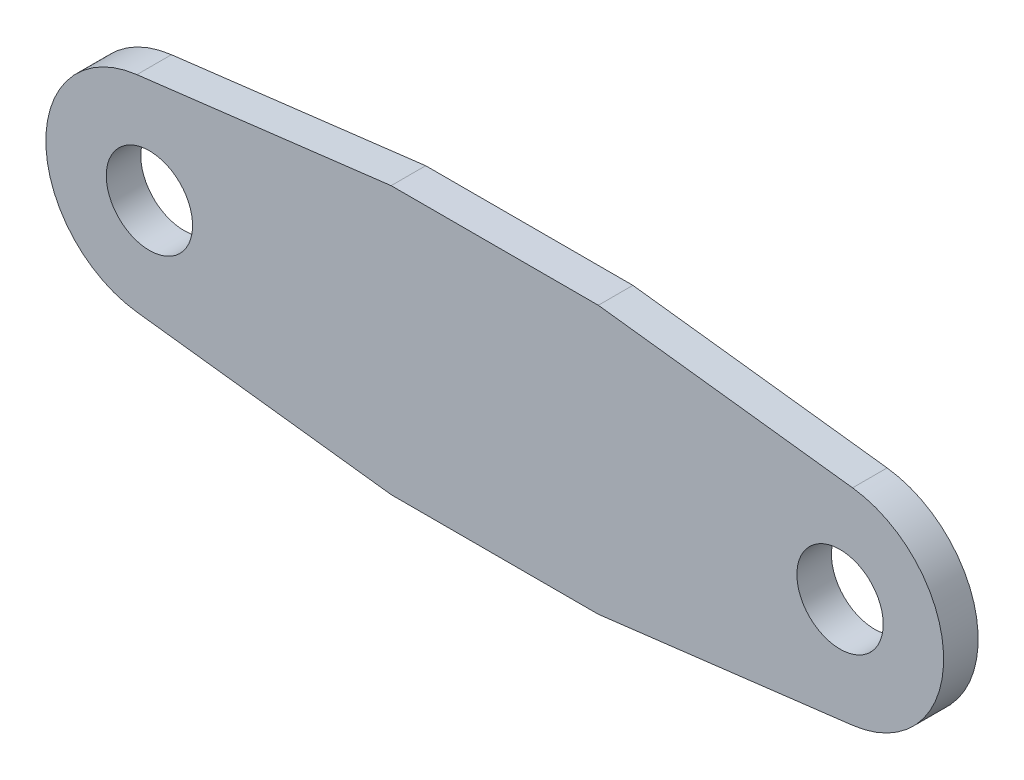
SolidWorks part; units mm, degrees
material "Thornel Mat VMA"
ref_plane "Alzado" through (0, 0, 0) normal (0, 0, 1) x (1, 0, 0)
ref_plane "Planta" through (0, 0, 0) normal (0, 1, 0) x (1, 0, 0)
ref_plane "Vista lateral" through (0, 0, 0) normal (1, 0, 0) x (0, 0, -1)
sketch "Croquis1" plane through (0, 0, 0) normal (0, 0, 1) x (1, 0, 0)
  line L0 (0, 0) -> (0, 3.875) construction
  line L5 (0, 0) -> (13, 0) construction
  line L6 (3, 3.875) -> (10.3628, 2.978)
  line L7 (-3, 3.875) -> (3, 3.875)
  line L8 (3, -3.875) -> (10.3628, -2.978)
  line L9 (-3, -3.875) -> (3, -3.875)
  line L10 (-3, -3.875) -> (-10.3628, -2.978)
  line L11 (-3, 3.875) -> (-10.3628, 2.978)
  arc A0 (10.3628, -2.978) -> (10.3628, 2.978) centre (10, 0) ccw
  circle A1 centre (10, 0) radius 1.25
  arc A2 (-10.3628, -2.978) -> (-10.3628, 2.978) centre (-10, 0) cw
  circle A3 centre (-10, 0) radius 1.25
  point P0 (0, 0)
  point P16 (0, -3.875)
  dimension "D2" = 6
  dimension "D4" = 2.5
  dimension "D3" = 3
extrude "Saliente-Extruir1" add sketch "Croquis1" along normal blind 1
